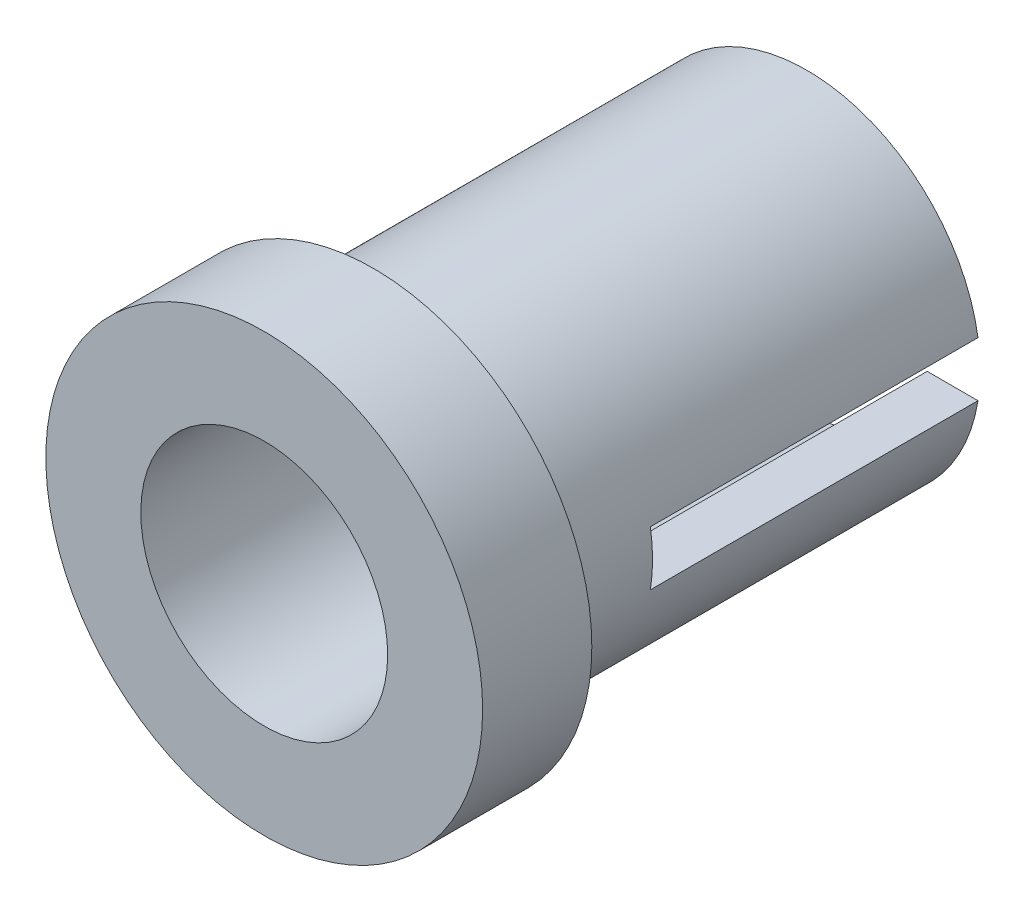
SolidWorks part; units mm, degrees
ref_plane "Front Plane" through (0, 0, 0) normal (0, 0, 1) x (1, 0, 0)
ref_plane "Top Plane" through (0, 0, 0) normal (0, 1, 0) x (1, 0, 0)
ref_plane "Right Plane" through (0, 0, 0) normal (1, 0, 0) x (0, 0, -1)
sketch "Sketch1" plane through (0, 0, 0) normal (0, 0, 1) x (1, 0, 0)
  circle A0 centre (0, 0) radius 1.1303
  circle A1 centre (0, 0) radius 1.5875
  dimension "D1" = 2.2606
  dimension "D2" = 3.175
extrude "Boss-Extrude1" add sketch "Sketch1" along normal blind 3.9688
sketch "Sketch2" plane through (0, 0, 3.9688) normal (0, 0, 1) x (1, 0, 0)
  circle A0 centre (0, 0) radius 2
  circle A1 centre (0, 0) radius 1.5875
  circle A2 centre (0, 0) radius 1.5875
  circle A5 centre (0, 0) radius 1.1303
  circle M2 centre (0, 0) radius 1.5875
  circle M3 centre (0, 0) radius 1.1303
  dimension "D2" = 4
  dimension "D1" = 0
extrude "Boss-Extrude2" add sketch "Sketch2" along normal blind 1 contours M2 M3 | A0 M2
sketch "Sketch3" plane through (0, 0, 0) normal (0, 0, -1) x (-1, 0, 0)
  line L1 (-2.1426, 0.25) -> (2.1426, 0.25)
  line L2 (-2.1426, 0.25) -> (-2.1426, -0.25)
  line L3 (-2.1426, -0.25) -> (2.1426, -0.25)
  line L4 (2.1426, 0.25) -> (2.1426, -0.25)
  line L5 (-2.1426, 0.25) -> (2.1426, -0.25) construction
  line L6 (-2.1426, -0.25) -> (2.1426, 0.25) construction
  point P0 (0, 0)
  dimension "D1" = 0.5
extrude "Cut-Extrude1" cut sketch "Sketch3" against normal blind 3
